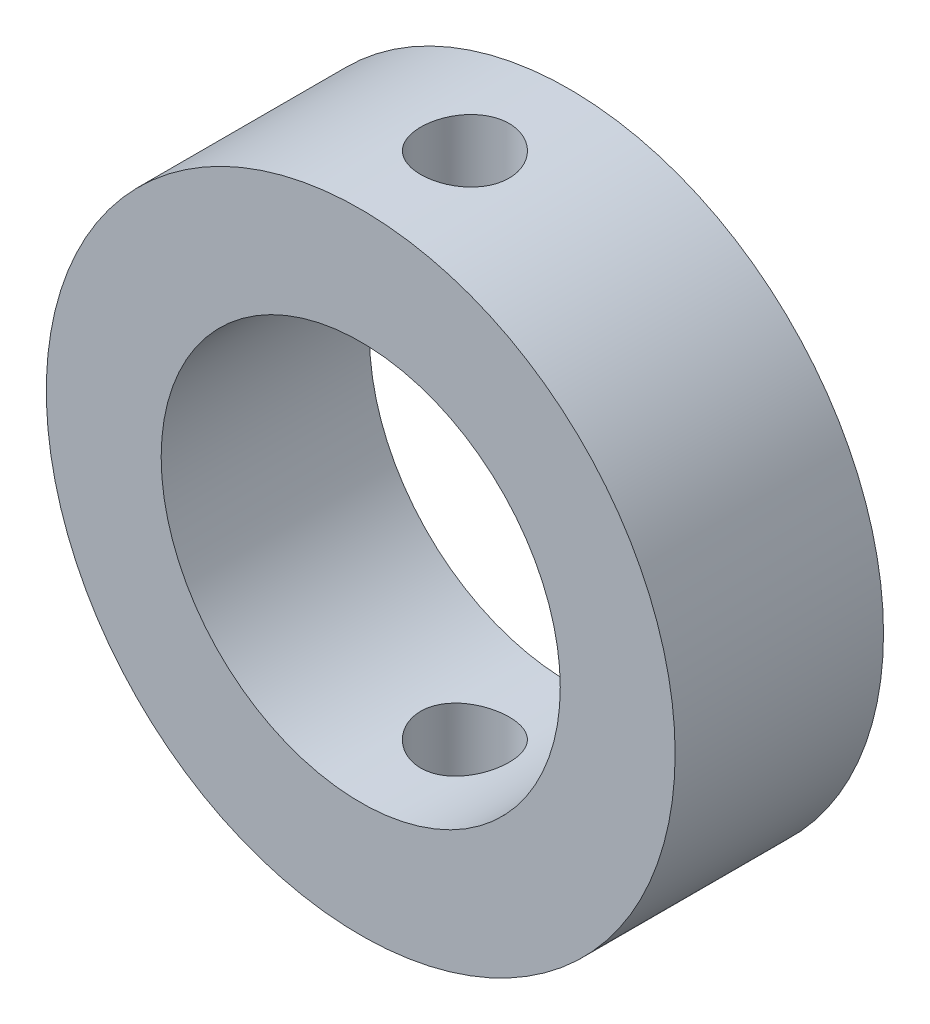
SolidWorks part; units mm, degrees
ref_plane "Front Plane" through (0, 0, 0) normal (0, 0, 1) x (1, 0, 0)
ref_plane "Top Plane" through (0, 0, 0) normal (0, 1, 0) x (1, 0, 0)
ref_plane "Right Plane" through (0, 0, 0) normal (1, 0, 0) x (0, 0, -1)
sketch "Sketch1" plane through (0, 0, 0) normal (0, 0, 1) x (1, 0, 0)
  circle A0 centre (0, 0) radius 57.338
  circle A1 centre (0, 0) radius 36.3911
extrude "Boss-Extrude2" add sketch "Sketch1" along normal blind 38
sketch "Sketch2" plane through (0, 0, 0) normal (0, 1, 0) x (1, 0, 0)
  line L0 (-57.338, -19) -> (57.338, -19) construction
  line L1 (0, 0) -> (0, -38) construction
  circle A0 centre (0, -19) radius 8.0694
extrude "Cut-Extrude1" cut sketch "Sketch2" against normal through all both and the other way through all
